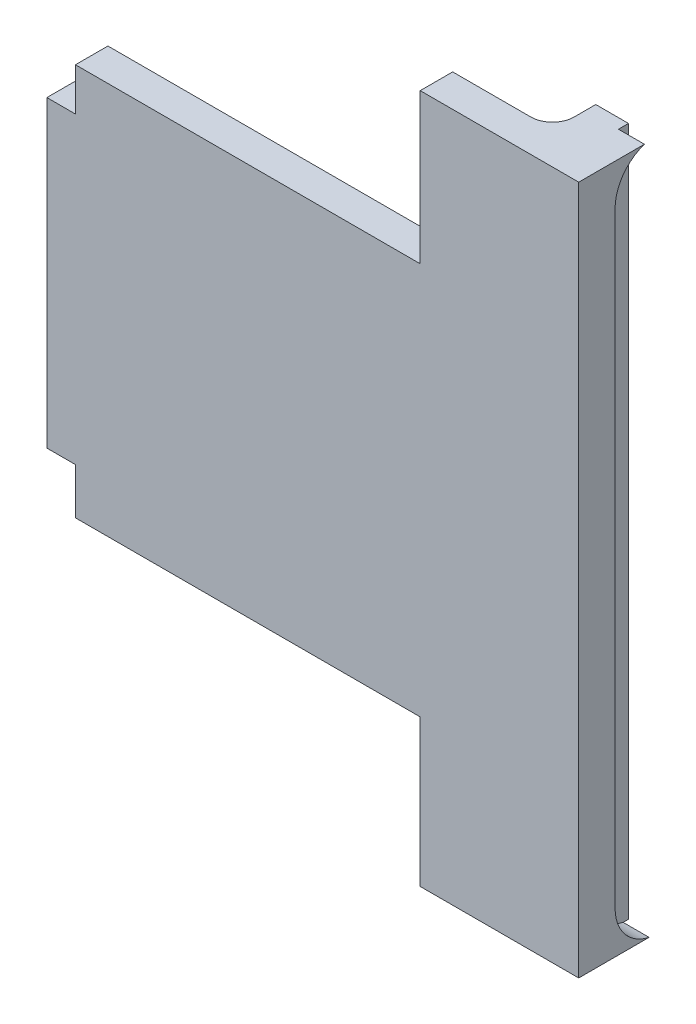
SolidWorks part; units mm, degrees
ref_plane "Front Plane" through (0, 0, 0) normal (0, 0, 1) x (1, 0, 0)
ref_plane "Top Plane" through (0, 0, 0) normal (0, 1, 0) x (1, 0, 0)
ref_plane "Right Plane" through (0, 0, 0) normal (1, 0, 0) x (0, 0, -1)
sketch "Sketch1" plane through (0, 0, 0) normal (0, 0, 1) x (1, 0, 0)
  line L0 (13.1507, -0.507) -> (13.1507, -7.2926)
  line L1 (20.4751, 24.5547) -> (13.1507, 24.5547)
  line L2 (20.4751, 24.5547) -> (20.4751, -7.2926)
  line L3 (20.4751, -7.2926) -> (13.1507, -7.2926)
  line L4 (13.1507, 24.5547) -> (13.1507, 17.6256)
  line L5 (-2.7796, 17.6256) -> (13.1507, 17.6256)
  line L6 (-2.7796, 17.6256) -> (-2.7796, 15.6524)
  line L7 (-2.7796, -0.507) -> (13.1507, -0.507)
  line L9 (-2.7796, 1.6239) -> (-2.7796, -0.507)
  line L10 (-4.1, 15.6524) -> (-2.7796, 15.6524)
  line L11 (-4.1, 15.6524) -> (-4.1, 1.6239)
  line L12 (-4.1, 1.6239) -> (-2.7796, 1.6239)
extrude "Boss-Extrude1" add sketch "Sketch1" against normal blind 1.5
sketch "Sketch2" plane through (0, 0, -1.5) normal (0, 0, -1) x (-1, 0, 0)
  line L0 (-20.4751, -7.2926) -> (-20.4751, 24.5547) construction
  line L1 (-20.4751, 24.5547) -> (-17.7616, 24.5547)
  line L2 (-20.4751, 24.5547) -> (-20.4751, -7.2926)
  line L3 (-20.4751, -7.2926) -> (-17.7616, -7.2926)
  line L4 (-17.7616, 24.5547) -> (-17.7616, -7.2926)
  line L5 (-13.1507, -7.2926) -> (-20.4751, -7.2926) construction
  line L6 (-17.7616, -7.2926) -> (-17.7616, -1.6387) construction
extrude "Boss-Extrude2" add sketch "Sketch2" along normal blind 2
sketch "Sketch3" plane through (0, 0, -1.5) normal (0, 0, -1) x (-1, 0, 0)
  line L0 (2.7796, 17.6256) -> (2.7796, 15.6524) construction
  line L2 (2.7796, 15.5892) -> (-9.4666, 15.5892)
  line L4 (2.7796, 1.649) -> (-9.4666, 1.649)
  line L5 (-9.4666, 15.5892) -> (-9.4666, 1.649)
  line L6 (2.7796, 15.5892) -> (4.1, 15.5892)
  line L7 (2.7796, 1.649) -> (2.7796, 1.6239)
  line L8 (2.7796, 1.6239) -> (4.1, 1.6239)
  line L9 (4.1, 15.5892) -> (4.1, 1.6239)
extrude "Cut-Extrude1" cut sketch "Sketch3" against normal blind 0.75
fillet "Fillet1" radius 1 1 edges at (17.7616, 8.6311, -1.5)
fillet "Fillet2" radius 0.3 3 edges at (3.3435, 1.649, -1.5) (9.4666, 8.6191, -1.5) (2.6833, 15.5892, -1.5)
sketch "Sketch4" plane through (20.4751, 0, 0) normal (1, 0, 0) x (0, 0, -1)
  line L0 (2.1794, 22.6613) -> (2.1794, -5.3387) construction
  line L1 (1.6794, 22.6613) -> (1.6794, -5.3387)
  line L2 (3.6794, 24.6613) -> (3.6794, -7.3387)
  arc A0 (2.1794, -5.3387) -> (3.6794, -6.8387) centre (3.6794, -5.3387) ccw construction
  arc A1 (3.6794, 24.1613) -> (2.1794, 22.6613) centre (3.6794, 22.6613) ccw construction
  arc A2 (2.1794, -5.3387) -> (3.6794, -6.8387) centre (3.6794, -5.3387) ccw construction
  arc A3 (3.6794, 24.1613) -> (2.1794, 22.6613) centre (3.6794, 22.6613) ccw construction
  arc A4 (3.6794, 24.6613) -> (1.6794, 22.6613) centre (3.6794, 22.6613) ccw
  arc A5 (1.6794, -5.3387) -> (3.6794, -7.3387) centre (3.6794, -5.3387) ccw
extrude "Cut-Extrude2" cut sketch "Sketch4" against normal blind 1.2
